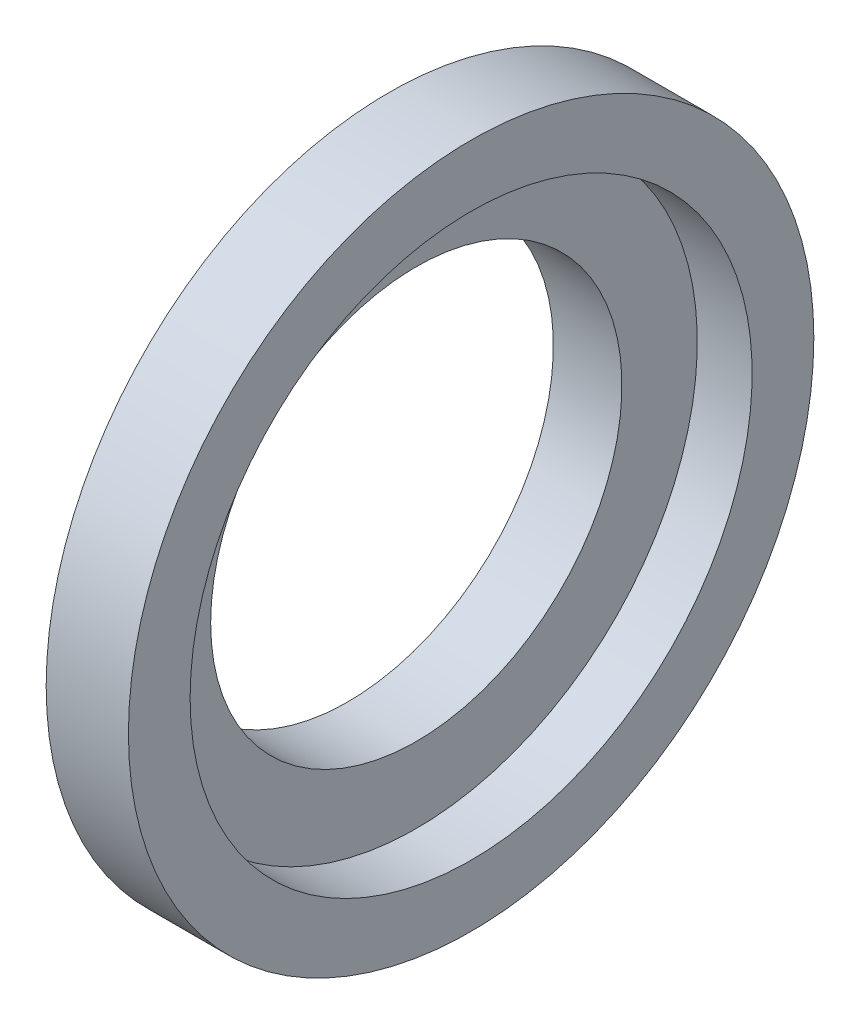
SolidWorks part; units mm, degrees
material "Plain Carbon Steel"
ref_plane "Front Plane" through (0, 0, 0) normal (0, 0, 1) x (1, 0, 0)
ref_plane "Top Plane" through (0, 0, 0) normal (0, 1, 0) x (1, 0, 0)
ref_plane "Right Plane" through (0, 0, 0) normal (1, 0, 0) x (0, 0, -1)
sketch "Sketch1" plane through (0, 0, 0) normal (0, 0, 1) x (1, 0, 0)
  line L0 (-40.274, 0) -> (47.3973, 0) construction
  line L1 (-26.5753, 30) -> (-16.5753, 30)
  line L2 (-16.5753, 30) -> (-16.5753, 41)
  line L3 (-16.5753, 41) -> (-8.5753, 41)
  line L4 (-8.5753, 41) -> (-8.5753, 50)
  line L5 (-8.5753, 50) -> (-20.5753, 50)
  line L6 (-20.5753, 50) -> (-26.5753, 36)
  line L7 (-26.5753, 36) -> (-26.5753, 30)
  point P5 (-21.5753, 30)
  dimension "D1" = 30
  dimension "D2" = 36
  dimension "D3" = 50
  dimension "D4" = 41
  dimension "D5" = 8
  dimension "D6" = 12
  dimension "D7" = 18
revolve "Revolve1" add sketch "Sketch1" angle 360 about L0
